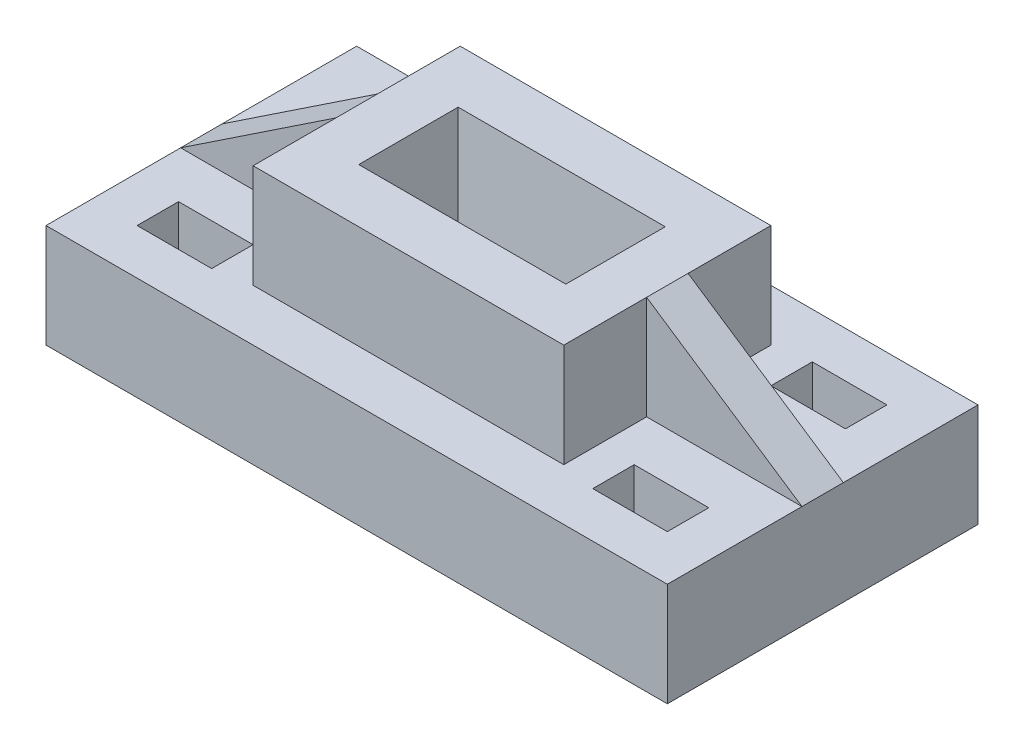
SolidWorks part; units mm, degrees
ref_plane "Front Plane" through (0, 0, 0) normal (0, 0, 1) x (1, 0, 0)
ref_plane "Top Plane" through (0, 0, 0) normal (0, 1, 0) x (1, 0, 0)
ref_plane "Right Plane" through (0, 0, 0) normal (1, 0, 0) x (0, 0, -1)
sketch "Sketch2" plane through (0, 0, 0) normal (0, 1, 0) x (1, 0, 0)
  line L1 (-75, 37.5) -> (75, 37.5)
  line L2 (-75, 37.5) -> (-75, -37.5)
  line L3 (-75, -37.5) -> (75, -37.5)
  line L4 (75, 37.5) -> (75, -37.5)
  line L5 (-75, 37.5) -> (75, -37.5) construction
  line L6 (-75, -37.5) -> (75, 37.5) construction
  point P0 (0, 0)
  dimension "D1" = 150
  dimension "D2" = 75
extrude "Boss-Extrude1" add sketch "Sketch2" along normal mid plane 25
sketch "Sketch3" plane through (0, 12.5, 0) normal (0, 1, 0) x (1, 0, 0)
  line L1 (-37.5, 25) -> (37.5, 25)
  line L2 (-37.5, 25) -> (-37.5, -25)
  line L3 (-37.5, -25) -> (37.5, -25)
  line L4 (37.5, 25) -> (37.5, -25)
  line L5 (-37.5, 25) -> (37.5, -25) construction
  line L6 (-37.5, -25) -> (37.5, 25) construction
  point P0 (0, 0)
  point P6 (0, 0)
  dimension "D1" = 75
  dimension "D2" = 50
extrude "Boss-Extrude3" add sketch "Sketch3" along normal blind 25
sketch "Sketch4" plane through (0, 37.5, 0) normal (0, 1, 0) x (1, 0, 0)
  line L1 (-25, 12) -> (25, 12)
  line L2 (-25, 12) -> (-25, -12)
  line L3 (-25, -12) -> (25, -12)
  line L4 (25, 12) -> (25, -12)
  line L5 (-25, 12) -> (25, -12) construction
  line L6 (-25, -12) -> (25, 12) construction
  point P0 (0, 0)
  dimension "D1" = 50
  dimension "D2" = 24
extrude "Cut-Extrude1" cut sketch "Sketch4" against normal blind 25 draft 5
sketch "Sketch5" plane through (0, 12.5, 0) normal (0, 1, 0) x (1, 0, 0)
  line L0 (-75, -37.5) -> (75, -37.5) construction
  line L1 (46, -16.5) -> (64, -16.5)
  line L2 (46, -16.5) -> (46, -26.5)
  line L3 (46, -26.5) -> (64, -26.5)
  line L4 (64, -16.5) -> (64, -26.5)
  line L5 (46, -16.5) -> (64, -26.5) construction
  line L6 (46, -26.5) -> (64, -16.5) construction
  line L7 (75, -37.5) -> (75, 37.5) construction
  point P0 (55, -21.5)
  dimension "D1" = 18
  dimension "D2" = 10
  dimension "D3" = 11
  dimension "D4" = 11
extrude "Cut-Extrude2" cut sketch "Sketch5" against normal through all
mirror "Mirror1" about plane through (0, 0, 0) normal (1, 0, 0) of "Cut-Extrude2"
mirror "Mirror2" about plane through (0, 0, 0) normal (0, 0, 1) of "Mirror1", "Cut-Extrude2"
sketch "Sketch6" plane through (0, 0, 0) normal (0, 0, 1) x (1, 0, 0)
  line L0 (-75, 12.5) -> (-37.5, 37.5)
rib "Rib1" sketch "Sketch6" sketch "Sketch6" thickness 10 extrusion direction parallel to sketch draft on no parameters "D1"=10
mirror "Mirror3" about plane through (0, 0, 0) normal (1, 0, 0) of "Rib1"
